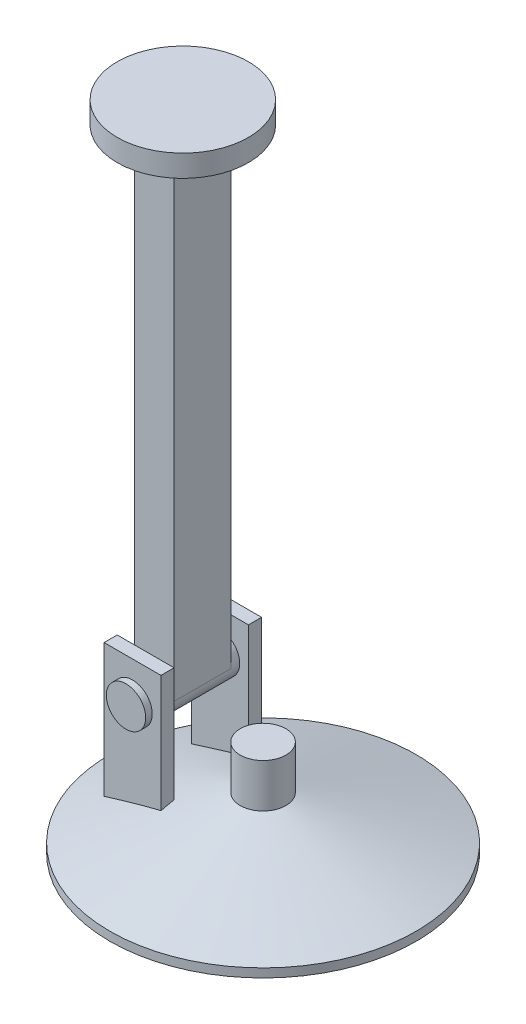
SolidWorks part; units mm, degrees
ref_plane "Front Plane" through (0, 0, 0) normal (0, 0, 1) x (1, 0, 0)
ref_plane "Top Plane" through (0, 0, 0) normal (0, 1, 0) x (1, 0, 0)
ref_plane "Right Plane" through (0, 0, 0) normal (1, 0, 0) x (0, 0, -1)
sketch "Sketch1" plane through (0, 0, 0) normal (0, 1, 0) x (1, 0, 0)
  circle A0 centre (0, 0) radius 35
  dimension "D1" = 70
ref_plane "Plane1" through (0, 10, 0) normal (0, 1, 0) x (1, 0, 0)
sketch "Sketch2" plane through (0, 10, 0) normal (0, 1, 0) x (1, 0, 0)
  circle A0 centre (0, 0) radius 5.2243
loft "Loft3" add profiles "Sketch1", "Sketch2"
sketch "Sketch8" plane through (0, 10, 0) normal (0, 1, 0) x (1, 0, 0)
  circle A0 centre (0, 0) radius 5.2243
extrude "Boss-Extrude1" add sketch "Sketch8" along normal blind 10
sketch "Sketch10" plane through (0, 0, 0) normal (0, 1, 0) x (1, 0, 0)
  circle A0 centre (0, 0) radius 35
ref_plane "Plane2" through (0, 0, 10) normal (0, 0, 1) x (1, 0, 0)
sketch "Sketch16" plane through (0, 0, 10) normal (0, 0, 1) x (1, 0, 0)
  line L0 (35, 0) -> (-35, 0) construction
  line L1 (-24.8409, 0) -> (-11.8409, 0)
  line L2 (-24.8409, 0) -> (-24.8409, 33)
  line L3 (-24.8409, 33) -> (-11.8409, 33)
  line L4 (-11.8409, 0) -> (-11.8409, 33)
  dimension "D1" = 33
  dimension "D2" = 13
extrude "Boss-Extrude5" add sketch "Sketch16" along normal mid plane 3
mirror "Mirror2" about plane through (0, 0, 0) normal (0, 0, 1) of "Boss-Extrude5"
sketch "Sketch19" plane through (0, 0, 0) normal (0, 0, 1) x (1, 0, 0)
  line L0 (-11.8409, 6.211) -> (-11.8409, 33) construction
  circle A0 centre (-18.3409, 24.3425) radius 4.5
  dimension "D1" = 9
  dimension "D2" = 6.5
extrude "Boss-Extrude6" add sketch "Sketch19" along normal mid plane 26
sketch "Sketch21" plane through (0, 0, 0) normal (0, 0, 1) x (1, 0, 0)
  line L1 (-22.8409, 24.3425) -> (-13.8409, 24.3425)
  line L2 (-22.8409, 24.3425) -> (-22.8409, 133.0025)
  line L3 (-22.8409, 133.0025) -> (-13.8409, 133.0025)
  line L4 (-13.8409, 24.3425) -> (-13.8409, 133.0025)
  circle A0 centre (-18.3409, 24.3425) radius 4.5 construction
  circle A1 centre (-18.3409, 24.3425) radius 4.5 construction
  dimension "D1" = 108.66
extrude "Boss-Extrude7" add sketch "Sketch21" along normal mid plane 13
sketch "Sketch22" plane through (0, 0, 0) normal (0, 1, 0) x (1, 0, 0)
  circle A0 centre (0, 0) radius 35
  dimension "D1" = 70
extrude "Boss-Extrude8" add sketch "Sketch22" against normal blind 2
sketch "Sketch23" plane through (0, 133.0025, 0) normal (0, 1, 0) x (1, 0, 0)
  line L0 (-18.3409, -6.5) -> (-18.3409, 6.5) construction
  line L1 (-13.8409, -6.5) -> (-22.8409, -6.5) construction
  line L2 (-13.8409, 6.5) -> (-22.8409, 6.5) construction
  line L3 (-22.8409, 0) -> (-13.8409, 0) construction
  line L4 (-22.8409, -6.5) -> (-22.8409, 6.5) construction
  line L5 (-13.8409, -6.5) -> (-13.8409, 6.5) construction
  circle A0 centre (-18.3409, 0) radius 15
  dimension "D1" = 30
extrude "Boss-Extrude9" add sketch "Sketch23" along normal blind 5
